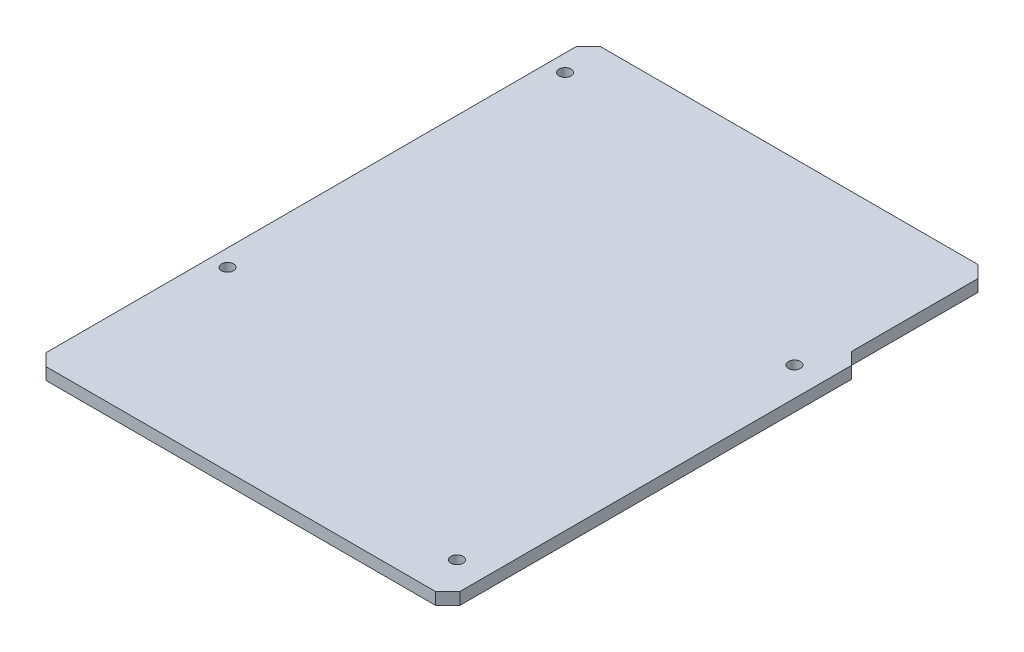
SolidWorks part; units mm, degrees
ref_plane "Front Plane" through (0, 0, 0) normal (0, 0, 1) x (1, 0, 0)
ref_plane "Top Plane" through (0, 0, 0) normal (0, 1, 0) x (1, 0, 0)
ref_plane "Right Plane" through (0, 0, 0) normal (1, 0, 0) x (0, 0, -1)
sketch "Sketch1" plane through (0, 0, 0) normal (0, 1, 0) x (1, 0, 0)
  line L0 (-45.8, 72.5) -> (-45.8, -72.5) construction
  line L1 (50, -72.5) -> (-50, -72.5)
  line L2 (50, -72.5) -> (50, 72.5)
  line L3 (50, 72.5) -> (-50, 72.5)
  line L4 (-50, -72.5) -> (-50, 72.5)
  line L5 (0, 72.5) -> (0, -72.5) construction
  line L6 (50, 0) -> (-50, 0) construction
  line L7 (45.8, 72.5) -> (45.8, -72.5) construction
  line L8 (-27.6364, 55.5) -> (-27.6364, 21) construction
  line L9 (-27.6364, -28.5) -> (-27.6364, -63) construction
  circle A0 centre (-45.8, 55.5) radius 1.5
  circle A1 centre (-45.8, 21) radius 1.5 construction
  circle A2 centre (-45.8, -28.5) radius 1.5
  circle A3 centre (-45.8, -63) radius 1.5 construction
  circle A4 centre (45.8, -63) radius 1.5
  circle A5 centre (45.8, -28.5) radius 1.5 construction
  circle A6 centre (45.8, 21) radius 1.5
  circle A7 centre (45.8, 55.5) radius 1.5 construction
  point P0 (0, 0)
  dimension "D7" = 3
  dimension "D1" = 100
  dimension "D2" = 145
  dimension "D3" = 91.6
  dimension "D4" = 17
  dimension "D5" = 51.5
  dimension "D6" = 101
extrude "Boss-Extrude1" add sketch "Sketch1" along normal blind 3
sketch "Sketch2" plane through (0, 3, 0) normal (0, 1, 0) x (1, 0, 0)
  line L0 (50, -72.5) -> (50, 72.5) construction
  line L1 (50, 65.5) -> (-50, 65.5)
  line L2 (50, 65.5) -> (50, 72.5)
  line L3 (50, 72.5) -> (-50, 72.5)
  line L4 (-50, 65.5) -> (-50, 72.5)
  line L5 (0, 72.5) -> (0, 65.5) construction
  line L6 (50, 69) -> (-50, 69) construction
  point P0 (0, 69)
  point P4 (0, 0)
  point P5 (0, 0)
  dimension "D1" = 7
extrude "Cut-Extrude1" cut sketch "Sketch2" against normal through all
sketch "Sketch3" plane through (0, 0, 0) normal (0, -1, 0) x (1, 0, 0)
  line L0 (50, 72.5) -> (53, 69.5)
  line L1 (53, 69.5) -> (53, -28)
  line L2 (53, -28) -> (50, -31)
  line L3 (50, -31) -> (50, 72.5)
  dimension "D1" = 3
  dimension "D2" = 10
extrude "Boss-Extrude2" add sketch "Sketch3" against normal up to surface (3 mm away) up to face at (0, 3, 3.5)
chamfer "Chamfer1" distance 3 angle 45 2 edges at (-50, 1.5, -65.5) (50, 1.5, -65.5)
chamfer "Chamfer2" distance 3 angle 45 1 edges at (-50, 1.5, 72.5)
